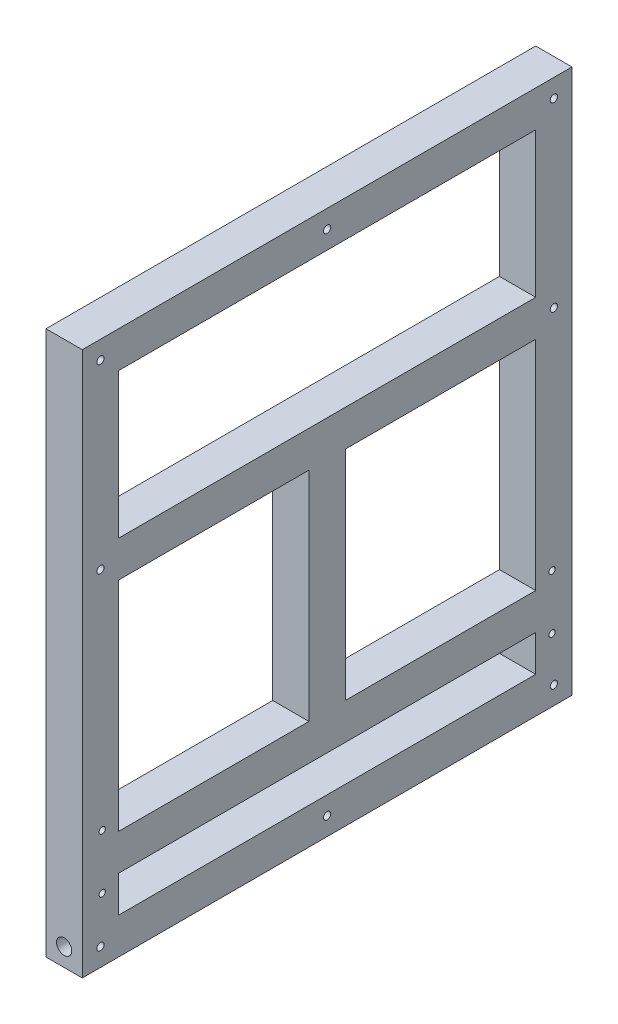
SolidWorks part; units mm, degrees
ref_plane "Front Plane" through (0, 0, 0) normal (0, 0, 1) x (1, 0, 0)
ref_plane "Top Plane" through (0, 0, 0) normal (0, 1, 0) x (1, 0, 0)
ref_plane "Right Plane" through (0, 0, 0) normal (1, 0, 0) x (0, 0, -1)
sketch "Sketch3" plane through (0, 0, 0) normal (0, 1, 0) x (1, 0, 0)
  line L1 (0, 0) -> (20, 0)
  line L2 (0, 0) -> (0, 20)
  line L3 (0, 20) -> (20, 20)
  line L4 (20, 0) -> (20, 20)
extrude "Boss-Extrude1" add sketch "Sketch3" along normal blind 300
sketch "Sketch5" plane through (0, 0, -20) normal (0, 0, -1) x (-1, 0, 0)
  line L0 (0, 300) -> (0, 0) construction
  line L1 (-20, 0) -> (0, 0)
  line L2 (-20, 0) -> (-20, 20)
  line L3 (-20, 20) -> (0, 20)
  line L4 (0, 0) -> (0, 20)
  line L7 (-20, 280) -> (0, 280)
  line L8 (0, 300) -> (0, 280)
  line L9 (-20, 300) -> (0, 300)
  line L10 (-20, 300) -> (-20, 280)
extrude "Boss-Extrude4" add sketch "Sketch5" along normal blind 250
sketch "Sketch8" plane through (0, 20, 0) normal (0, 1, 0) x (1, 0, 0)
  line L0 (0, 270) -> (0, 20) construction
  line L1 (20, 270) -> (0, 270)
  line L2 (20, 270) -> (20, 250)
  line L3 (20, 250) -> (0, 250)
  line L4 (0, 270) -> (0, 250)
extrude "Boss-Extrude5" add sketch "Sketch8" along normal blind 260
sketch "Sketch13" plane through (0, 0, 0) normal (-1, 0, 0) x (0, 0, 1)
  line L0 (-250, 40) -> (-250, 60)
  line L1 (-250, 280) -> (-250, 20) construction
  line L2 (-250, 60) -> (-20, 60)
  line L4 (-20, 280) -> (-20, 20) construction
  line L5 (-20, 60) -> (-20, 40)
  line L6 (-20, 40) -> (-250, 40)
extrude "Boss-Extrude7" add sketch "Sketch13" against normal blind 20
sketch "Sketch14" plane through (20, 0, 0) normal (1, 0, 0) x (0, 0, -1)
  line L1 (20, 280) -> (20, 60) construction
  line L2 (20, 200) -> (125, 200)
  line L3 (250, 280) -> (250, 60) construction
  line L4 (250, 200) -> (250, 180)
  line L5 (250, 180) -> (145, 180)
  line L6 (20, 180) -> (20, 200)
  line L7 (250, 20) -> (20, 20) construction
  line L8 (250, 280) -> (20, 280) construction
  line L9 (125, 280) -> (145, 280)
  line L11 (145, 20) -> (125, 20)
  line L13 (145, 200) -> (250, 200)
  line L14 (125, 180) -> (20, 180)
  line L17 (125, 200) -> (145, 200)
  line L18 (145, 180) -> (125, 180)
  line M11 (20, 60) -> (20, 280)
  line M13 (250, 280) -> (250, 60)
extrude "Boss-Extrude8" add sketch "Sketch14" against normal blind 20 contours L18 L5 L13 L17 L2 L14 M13 M11
sketch "Sketch15" plane through (20, 0, 0) normal (1, 0, 0) x (0, 0, -1)
  line L1 (250, 180) -> (20, 180) construction
  line L2 (20, 60) -> (250, 60) construction
  line L3 (125, 60) -> (145, 60)
  line L4 (145, 60) -> (145, 180)
  line L5 (145, 180) -> (125, 180)
  line L6 (125, 60) -> (125, 180)
extrude "Boss-Extrude9" add sketch "Sketch15" against normal blind 20
sketch "Sketch16" plane through (20, 0, 0) normal (1, 0, 0) x (0, 0, -1)
  circle A0 centre (10, 290) radius 2
  circle A1 centre (10, 190) radius 2
  circle A2 centre (10, 10) radius 2
  circle A3 centre (135, 10) radius 2
  circle A4 centre (135, 290) radius 2
  circle A5 centre (260, 10) radius 2
  circle A6 centre (260, 190) radius 2
  circle A7 centre (260, 290) radius 2
extrude "Cut-Extrude1" cut sketch "Sketch16" against normal blind 20
sketch "Sketch17" plane through (0, 0, -270) normal (0, 0, -1) x (-1, 0, 0)
  circle A0 centre (-10, 10) radius 4.2
extrude "Cut-Extrude2" cut sketch "Sketch17" against normal blind 270
sketch "Sketch19" plane through (20, 0, 0) normal (1, 0, 0) x (0, 0, -1)
  circle A0 centre (11, 35) radius 1.75
  circle A1 centre (11, 65) radius 1.75
  circle A2 centre (259, 35) radius 1.75
  circle A3 centre (259, 65) radius 1.75
extrude "Cut-Extrude3" cut sketch "Sketch19" against normal blind 78
